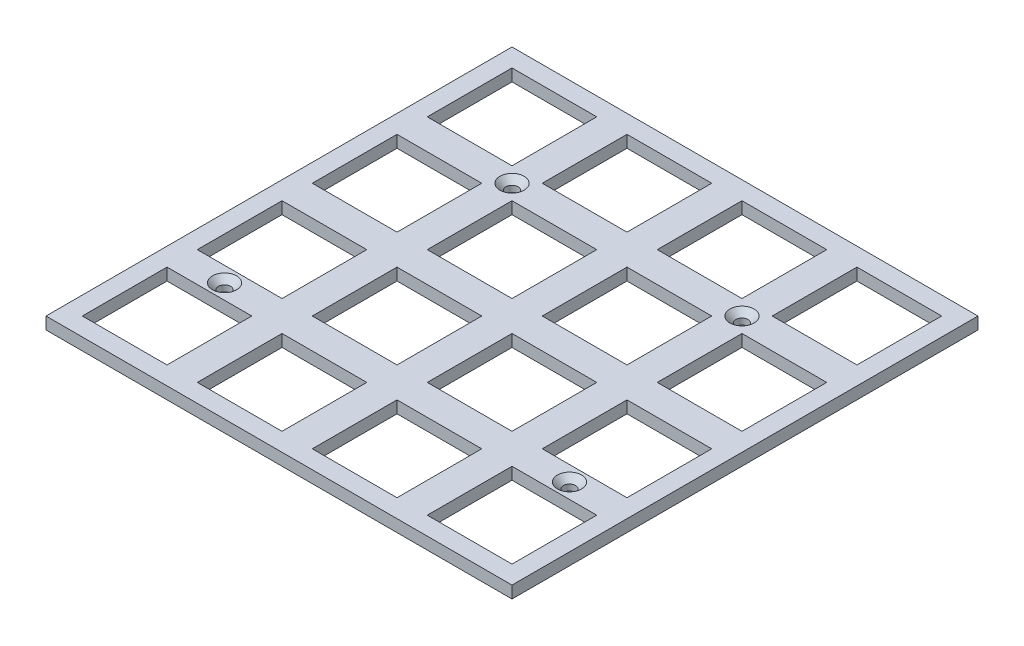
SolidWorks part; units mm, degrees
ref_plane "Front Plane" through (0, 0, 0) normal (0, 0, 1) x (1, 0, 0)
ref_plane "Top Plane" through (0, 0, 0) normal (0, 1, 0) x (1, 0, 0)
ref_plane "Right Plane" through (0, 0, 0) normal (1, 0, 0) x (0, 0, -1)
sketch "Sketch5" plane through (0, 0, 0) normal (1, 0, 0) x (0, 0, -1)
  line L0 (0, 0) -> (0, 13.4604) construction
sketch "Sketch1" plane through (0, 0, 0) normal (0, 1, 0) x (1, 0, 0)
  line L5 (-16.5, 21.5) -> (-16.5, 35.5)
  line L6 (-38.5, -38.5) -> (38.5, -38.5)
  line L11 (-38.5, -38.5) -> (-38.5, 38.5)
  line L12 (-38.5, 38.5) -> (38.5, 38.5)
  line L72 (38.5, -38.5) -> (38.5, 38.5)
  line L88 (-38.5, -38.5) -> (38.5, 38.5) construction
  line L89 (-38.5, 38.5) -> (38.5, -38.5) construction
  line L90 (-35.5, 21.5) -> (-21.5, 21.5)
  line L91 (-35.5, 21.5) -> (-35.5, 35.5)
  line L92 (-35.5, 35.5) -> (-21.5, 35.5)
  line L93 (-21.5, 21.5) -> (-21.5, 35.5)
  line L94 (-35.5, 21.5) -> (-21.5, 35.5) construction
  line L95 (-35.5, 35.5) -> (-21.5, 21.5) construction
  line L96 (-16.5, 21.5) -> (-2.5, 21.5)
  line L97 (-2.5, 21.5) -> (-2.5, 35.5)
  line L98 (-16.5, 35.5) -> (-2.5, 35.5)
  line L99 (2.5, 21.5) -> (2.5, 35.5)
  line L100 (2.5, 21.5) -> (16.5, 21.5)
  line L101 (16.5, 21.5) -> (16.5, 35.5)
  line L102 (2.5, 35.5) -> (16.5, 35.5)
  line L103 (21.5, 21.5) -> (21.5, 35.5)
  line L104 (21.5, 21.5) -> (35.5, 21.5)
  line L105 (35.5, 21.5) -> (35.5, 35.5)
  line L106 (21.5, 35.5) -> (35.5, 35.5)
  line L107 (-16.5, 2.5) -> (-16.5, 16.5)
  line L108 (-16.5, 2.5) -> (-2.5, 2.5)
  line L109 (-2.5, 2.5) -> (-2.5, 16.5)
  line L110 (-16.5, 16.5) -> (-2.5, 16.5)
  line L111 (2.5, 2.5) -> (2.5, 16.5)
  line L112 (2.5, 2.5) -> (16.5, 2.5)
  line L113 (16.5, 2.5) -> (16.5, 16.5)
  line L114 (2.5, 16.5) -> (16.5, 16.5)
  line L115 (21.5, 2.5) -> (21.5, 16.5)
  line L116 (21.5, 2.5) -> (35.5, 2.5)
  line L117 (35.5, 2.5) -> (35.5, 16.5)
  line L118 (21.5, 16.5) -> (35.5, 16.5)
  line L119 (-16.5, -16.5) -> (-16.5, -2.5)
  line L120 (-16.5, -16.5) -> (-2.5, -16.5)
  line L121 (-2.5, -16.5) -> (-2.5, -2.5)
  line L122 (-16.5, -2.5) -> (-2.5, -2.5)
  line L123 (2.5, -16.5) -> (2.5, -2.5)
  line L124 (2.5, -16.5) -> (16.5, -16.5)
  line L125 (16.5, -16.5) -> (16.5, -2.5)
  line L126 (2.5, -2.5) -> (16.5, -2.5)
  line L127 (21.5, -16.5) -> (21.5, -2.5)
  line L128 (21.5, -16.5) -> (35.5, -16.5)
  line L129 (35.5, -16.5) -> (35.5, -2.5)
  line L130 (21.5, -2.5) -> (35.5, -2.5)
  line L131 (-16.5, -35.5) -> (-16.5, -21.5)
  line L132 (-16.5, -35.5) -> (-2.5, -35.5)
  line L133 (-2.5, -35.5) -> (-2.5, -21.5)
  line L134 (-16.5, -21.5) -> (-2.5, -21.5)
  line L135 (2.5, -35.5) -> (2.5, -21.5)
  line L136 (2.5, -35.5) -> (16.5, -35.5)
  line L137 (16.5, -35.5) -> (16.5, -21.5)
  line L138 (2.5, -21.5) -> (16.5, -21.5)
  line L139 (21.5, -35.5) -> (21.5, -21.5)
  line L140 (21.5, -35.5) -> (35.5, -35.5)
  line L141 (35.5, -35.5) -> (35.5, -21.5)
  line L142 (21.5, -21.5) -> (35.5, -21.5)
  line L143 (-35.5, 2.5) -> (-35.5, 16.5)
  line L144 (-35.5, 2.5) -> (-21.5, 2.5)
  line L145 (-21.5, 2.5) -> (-21.5, 16.5)
  line L146 (-35.5, 16.5) -> (-21.5, 16.5)
  line L147 (-35.5, -16.5) -> (-35.5, -2.5)
  line L148 (-35.5, -16.5) -> (-21.5, -16.5)
  line L149 (-21.5, -16.5) -> (-21.5, -2.5)
  line L150 (-35.5, -2.5) -> (-21.5, -2.5)
  line L151 (-35.5, -35.5) -> (-35.5, -21.5)
  line L152 (-35.5, -35.5) -> (-21.5, -35.5)
  line L153 (-21.5, -35.5) -> (-21.5, -21.5)
  line L154 (-35.5, -21.5) -> (-21.5, -21.5)
  line L155 (-35.5, 21.5) -> (-16.5, 21.5) construction
  line L156 (-35.5, 21.5) -> (-35.5, 2.5) construction
  point P0 (0, 0)
  point P6 (-28.5, 28.5)
  dimension "D1" = 3
  dimension "D2" = 14
  dimension "D5" = 90
  dimension "D6" = 19
  dimension "D7" = 19
  dimension "D3" = 4
  dimension "D8" = 77
  dimension "D9" = 5
  dimension "D4" = 4
extrude "Boss-Extrude1" add sketch "Sketch1" along normal blind 2
sketch "Sketch2" plane through (0, 2, 0) normal (0, 1, 0) x (1, 0, 0)
  line L0 (-28.5, -16.5) -> (-28.5, -21.5) construction
  line L5 (-35.5, -16.5) -> (-21.5, -16.5) construction
  line L7 (-21.5, -21.5) -> (-35.5, -21.5) construction
  line L8 (-28.5, -19) -> (0, -19) construction
  line L9 (-21.5, 16.5) -> (-16.5, 16.5) construction
  line L10 (-21.5, 16.5) -> (-21.5, 21.5) construction
  line L11 (-21.5, 21.5) -> (-16.5, 21.5) construction
  line L12 (-16.5, 16.5) -> (-16.5, 21.5) construction
  line L15 (-21.5, 16.5) -> (-16.5, 21.5) construction
  line L20 (-21.5, 21.5) -> (-16.5, 16.5) construction
  line L22 (-19, 19) -> (0, 19) construction
  circle A0 centre (-19, 19) radius 1
  circle A1 centre (-28.5, -19) radius 1
  point P2 (0, 0)
  point P8 (-19, 19)
  point P17 (-28.5, -19)
  dimension "D1" = 2
  dimension "D2" = 2
  dimension "D3" = 19
  dimension "D4" = 28.5
extrude "Cut-Extrude1" cut sketch "Sketch2" against normal up to surface (2 mm away) up to face at (0, 0, 0)
sketch "Sketch3" plane through (0, 2, 0) normal (0, 1, 0) x (1, 0, 0)
  circle A2 centre (-19, 19) radius 2
  circle A3 centre (-19, 19) radius 2
  circle A4 centre (-28.5, -19) radius 2
  circle A5 centre (-28.5, -19) radius 2
  point P0 (-28.5, 19)
  dimension "D1" = 1
  dimension "D2" = 1
extrude "Cut-Extrude2" [suppressed] cut sketch "Sketch3" against normal blind 1
chamfer "Chamfer1" distance 1 angle 45 2 edges at (-19, 2, -18) (-28.5, 2, 20)
mirror "Mirror1" about plane through (0, 0, 0) normal (1, 0, 0) of "Chamfer1", "Cut-Extrude1"
equation "\"screwhole\"=2"
equation "\"D2@Sketch2\"=\"screwhole\""
equation "\"D1@Sketch2\"=\"screwhole\""
